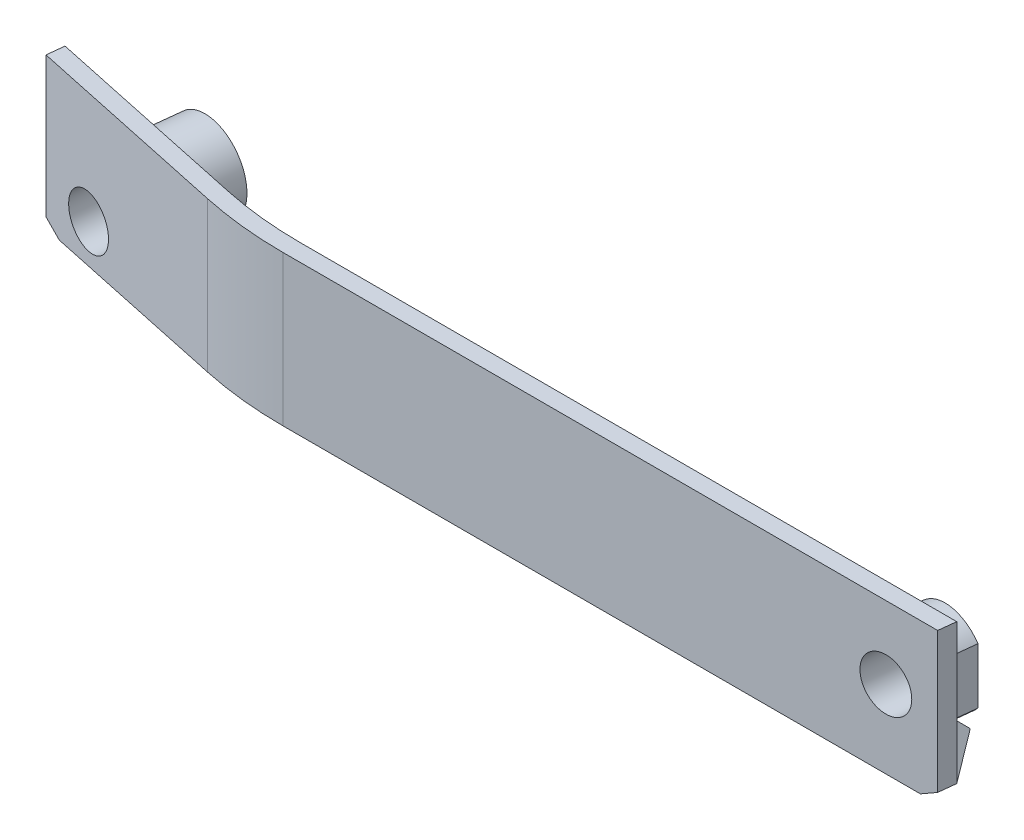
SolidWorks part; units mm, degrees
material "ABS"
ref_plane "Front Plane" through (0, 0, 0) normal (0, 0, 1) x (1, 0, 0)
ref_plane "Top Plane" through (0, 0, 0) normal (0, 1, 0) x (1, 0, 0)
ref_plane "Right Plane" through (0, 0, 0) normal (1, 0, 0) x (0, 0, -1)
sketch "Sketch1" plane through (0, 0, 0) normal (0, 0, 1) x (1, 0, 0)
  line L1 (62.4216, 92.5065) -> (-14.0771, 92.5065)
  line L2 (62.4216, 92.5065) -> (62.4216, 108.8462)
  line L3 (62.4216, 108.8462) -> (-14.0771, 108.8462)
  line L4 (-14.0771, 92.5065) -> (-14.0771, 108.8462)
extrude "Extrude1" add sketch "Sketch1" along normal blind 2
sketch "Sketch2" plane through (-0.8167, 0, 3.8341) normal (-0.2083, 0, 0.9781) x (0.9781, 0, 0.2083)
  line L1 (-23.1433, 108.8462) -> (-47.8069, 108.8462)
  line L2 (-23.1433, 108.8462) -> (-23.1433, 92.5065)
  line L3 (-23.1433, 92.5065) -> (-47.8069, 92.5065)
  line L4 (-47.8069, 108.8462) -> (-47.8069, 92.5065)
extrude "Extrude2" add sketch "Sketch2" along normal blind 2
sketch "Sketch3" plane through (0, 92.5065, 0) normal (0, -1, 0) x (1, 0, 0)
  line L0 (-14.0771, 2) -> (-14.0771, 0) construction
  line L1 (-23.8688, 0.9687) -> (-23.4521, -0.9874) construction
  line L2 (-14.0771, 2) -> (-14.0771, 0)
  line L3 (-23.8688, 0.9687) -> (-23.4521, -0.9874)
  line L4 (-14.0771, 2) -> (62.4216, 2) construction
  line L5 (-47.9913, -4.1696) -> (-23.8688, 0.9687) construction
  arc A0 (-14.0771, 0) -> (-23.4521, -0.9874) centre (-14.0771, -45) ccw construction
  arc A1 (-14.0771, 0) -> (-23.4521, -0.9874) centre (-14.0771, -45) ccw
  arc A2 (-23.8688, 0.9687) -> (-14.0771, 2) centre (-14.0771, -45) cw
extrude "Extrude3" add sketch "Sketch3" against normal up to vertex (16.3397 mm away)
sketch "Sketch4" plane through (0, 69.3799, -40.0565) normal (0, -0.866, 0.5) x (1, 0, 0)
  line L0 (48.9959, 28.9327) -> (66.3393, 48.5496)
  line L1 (66.3393, 48.5496) -> (-14.0771, 48.5496)
  line L2 (-14.0771, 48.5496) -> (-14.0771, 28.9327)
  line L3 (-14.0771, 28.9327) -> (48.9959, 28.9327)
  line L4 (-14.0771, 28.9327) -> (-14.0771, 32.9327) construction
  point P8 (62.4216, 46.2532)
  point P9 (63.6151, 46.2532)
  point P10 (0, 0)
  point P11 (-14.0771, 49.0307)
  point P12 (-14.0771, 49.1569)
  point P13 (-10.1138, 48.8448)
  point P16 (66.3393, 48.5496)
extrude "Extrude4" add sketch "Sketch4" along normal blind 2
sketch "Sketch5" plane through (8.1409, 67.6824, -38.219) normal (-0.1042, -0.866, 0.489) x (0.9946, -0.0907, 0.0512)
  line L0 (-39.5227, 25.5824) -> (-28.6238, 27.5929)
  line L1 (-28.6238, 27.5929) -> (-32.3486, 47.7849)
  line L2 (-32.3486, 47.7849) -> (-60.1606, 42.2516)
  line L3 (-60.1606, 42.2516) -> (-39.5227, 25.5824)
  line L4 (-28.6238, 27.5929) -> (-29.3494, 31.5265) construction
extrude "Extrude5" add sketch "Sketch5" along normal blind 2
sketch "Sketch6" plane through (-24.3964, 42.5158, -2.7105) normal (0.4969, -0.866, 0.0552) x (0.8678, 0.4959, -0.0316)
  line L1 (80.9412, -17.7931) -> (104.9625, -17.7931)
  line L2 (80.9412, -17.7931) -> (80.9412, 15.7562)
  line L3 (80.9412, 15.7562) -> (104.9625, 15.7562)
  line L4 (104.9625, -17.7931) -> (104.9625, 15.7562)
extrude "Cut-Extrude2" cut sketch "Sketch6" along normal blind 5
sketch "Sketch7" plane through (61.6605, 0, 6.8507) normal (0.9939, 0, 0.1104) x (0.1104, 0, -0.9939)
  line L1 (13.2772, 88.5524) -> (-6.6051, 88.5524)
  line L2 (13.2772, 88.5524) -> (13.2772, 111.3113)
  line L3 (13.2772, 111.3113) -> (-6.6051, 111.3113)
  line L4 (-6.6051, 88.5524) -> (-6.6051, 111.3113)
extrude "Cut-Extrude3" cut sketch "Sketch7" along normal blind 5
sketch "Sketch8" plane through (0, 83.8462, 0) normal (0, -1, 0) x (1, 0, 0)
  line L1 (51.8818, -41.4732) -> (-37.3666, -41.4732)
  line L2 (51.8818, -41.4732) -> (51.8818, -5.1993)
  line L3 (51.8818, -5.1993) -> (-37.3666, -5.1993)
  line L4 (-37.3666, -41.4732) -> (-37.3666, -5.1993)
  point P4 (51.8818, -5.1993)
extrude "Cut-Extrude4" cut sketch "Sketch8" along normal blind 5
sketch "Sketch9" plane through (0, 0, 2) normal (0, 0, 1) x (1, 0, 0)
  line L1 (66.3711, 84.8117) -> (-39.3929, 84.8117)
  line L2 (66.3711, 84.8117) -> (66.3711, 102.5326)
  line L3 (66.3711, 102.5326) -> (-39.3929, 102.5326)
  line L4 (-39.3929, 84.8117) -> (-39.3929, 102.5326)
extrude "Cut-Extrude5" cut sketch "Sketch9" along normal blind 5
sketch "Sketch10" plane through (-1.2334, 0, 5.7902) normal (-0.2083, 0, 0.9781) x (0.9781, 0, 0.2083)
  line L1 (-17.9488, 88.9283) -> (-52.7069, 88.9283)
  line L2 (-17.9488, 88.9283) -> (-17.9488, 98.0187)
  line L3 (-17.9488, 98.0187) -> (-52.7069, 98.0187)
  line L4 (-52.7069, 88.9283) -> (-52.7069, 98.0187)
extrude "Cut-Extrude6" cut sketch "Sketch10" along normal blind 5
sketch "Sketch11" plane through (-47.6668, 0, -5.2959) normal (-0.9939, 0, -0.1104) x (-0.1104, 0, 0.9939)
  line L1 (20.6941, 80.3783) -> (-22.3651, 80.3783)
  line L2 (20.6941, 80.3783) -> (20.6941, 112.8769)
  line L3 (20.6941, 112.8769) -> (-22.3651, 112.8769)
  line L4 (-22.3651, 80.3783) -> (-22.3651, 112.8769)
extrude "Cut-Extrude7" cut sketch "Sketch11" along normal blind 5
sketch "Sketch12" plane through (27.8948, 48.6125, 3.0992) normal (-0.4969, -0.866, -0.0552) x (0.8678, -0.4959, -0.0316)
  line L1 (-61.2127, -6.4785) -> (-91.776, -6.4785)
  line L2 (-61.2127, -6.4785) -> (-61.2127, -25.6421)
  line L3 (-61.2127, -25.6421) -> (-91.776, -25.6421)
  line L4 (-91.776, -6.4785) -> (-91.776, -25.6421)
extrude "Cut-Extrude8" cut sketch "Sketch12" along normal blind 5 contours L2 L1 L4 L3
sketch "Sketch15" plane through (-22.6354, 0, -4.8215) normal (0.9781, 0, 0.2083) x (0.2083, 0, -0.9781)
  line L5 (-5.9201, 92.5065) -> (-5.9201, 91.3518)
  line L6 (-5.9201, 91.3518) -> (7.0799, 83.8462)
  line L7 (7.0799, 83.8462) -> (11.0799, 83.8462)
  line L8 (11.0799, 83.8462) -> (-3.9201, 92.5065)
  line L9 (-3.9201, 92.5065) -> (-5.9201, 92.5065)
  line L10 (-5.9201, 92.5065) -> (-5.9201, 91.3518)
  line L11 (-5.9201, 91.3518) -> (7.0799, 83.8462)
  line L12 (7.0799, 83.8462) -> (11.0799, 83.8462)
  line L13 (11.0799, 83.8462) -> (-3.9201, 92.5065)
  line L14 (-3.9201, 92.5065) -> (-5.9201, 92.5065)
  dimension "D1" = 0
sweep "Sweep1" add profiles "Sketch15" path edge at (-18.7906, 92.5065, -0.2475)
sketch "Sketch16" plane through (0, 67.6478, -39.0565) normal (0, -0.866, 0.5) x (1, 0, 0)
  line L0 (-8.0771, 24.6778) -> (-8.0771, 40.9697) construction
  line L1 (-14.0771, 24.6778) -> (-14.0771, 40.9697)
  line L2 (-2.0771, 24.6778) -> (-2.0771, 40.9697)
  line L3 (-14.0771, 47.408) -> (-14.0771, 32.3968) construction
  arc A0 (-14.0771, 24.6778) -> (-2.0771, 24.6778) centre (-8.0771, 24.6778) ccw
  arc A1 (-2.0771, 40.9697) -> (-14.0771, 40.9697) centre (-8.0771, 40.9697) ccw
  point P2 (-8.0771, 32.8237)
  point P9 (-8.0771, 40.9697)
  dimension "D1" = 6
extrude "Cut-Extrude9" cut sketch "Sketch16" against normal blind 5
ref_plane "Plane2" through (1.2028, 0, -10.8262) normal (-0.1104, 0, 0.9939) x (0.9939, 0, 0.1104)
sketch "Sketch17" plane through (1.2028, 0, -10.8262) normal (-0.1104, 0, 0.9939) x (0.9939, 0, 0.1104)
  line L0 (-45.7601, 98.5532) -> (-45.7601, 93.7767)
  line L1 (-45.7601, 93.7767) -> (-40.804, 90.9152)
  line L2 (-32.4242, 85.8462) -> (-43.9601, 92.5065) construction
  line L3 (-45.9601, 93.6612) -> (-45.9601, 98.8462) construction
  line L4 (59.8399, 103.6433) -> (59.8399, 97.1441)
  line L5 (60.0399, 106.8462) -> (60.0399, 93.6612) construction
  circle A0 centre (-41.5476, 95.8596) radius 1.6
  arc A1 (-40.804, 90.9152) -> (-45.7601, 98.5532) centre (-41.5476, 95.8596) ccw
  circle A2 centre (56.0399, 100.3937) radius 1.6
  arc A3 (59.8399, 103.6433) -> (59.8399, 97.1441) centre (56.0399, 100.3937) ccw
  dimension "D1" = 3.2
  dimension "D2" = 3.2
  dimension "D3" = 10
  dimension "D4" = 10
  dimension "D5" = 0.2
  dimension "D6" = 0.2
  dimension "D7" = 0.2
extrude "Extrude6" add sketch "Sketch17" along normal up to next
ref_plane "Plane3" through (0.982, 0, -8.8385) normal (-0.1104, 0, 0.9939) x (0.9939, 0, 0.1104)
sketch "Sketch18" plane through (0.982, 0, -8.8385) normal (-0.1104, 0, 0.9939) x (0.9939, 0, 0.1104)
  circle A0 centre (-41.5476, 95.8596) radius 3
  circle A1 centre (56.0399, 100.3937) radius 3
  dimension "D1" = 6
extrude "Cut-Extrude10" cut sketch "Sketch18" along normal blind 46
